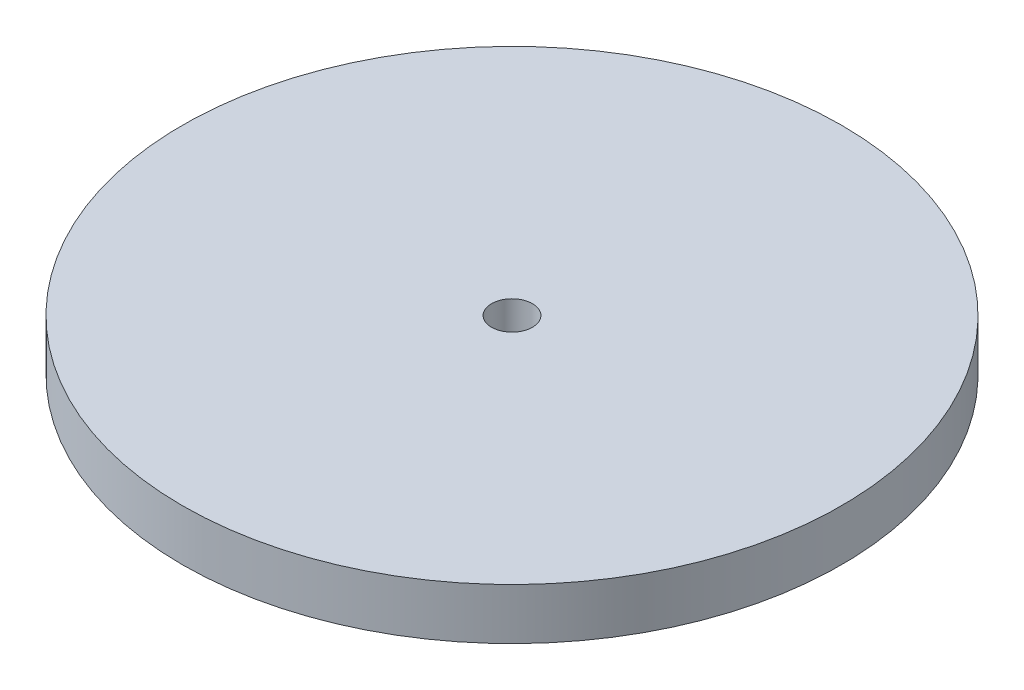
SolidWorks part; units mm, degrees
ref_plane "Front Plane" through (0, 0, 0) normal (0, 0, 1) x (1, 0, 0)
ref_plane "Top Plane" through (0, 0, 0) normal (0, 1, 0) x (1, 0, 0)
ref_plane "Right Plane" through (0, 0, 0) normal (1, 0, 0) x (0, 0, -1)
sketch "Sketch1" plane through (0, 0, 0) normal (0, 1, 0) x (1, 0, 0)
  circle A0 centre (0, 0) radius 32.2
  circle A1 centre (0, 0) radius 2
  dimension "D1" = 64.4
  dimension "D2" = 4
extrude "Boss-Extrude1" add sketch "Sketch1" along normal blind 5
